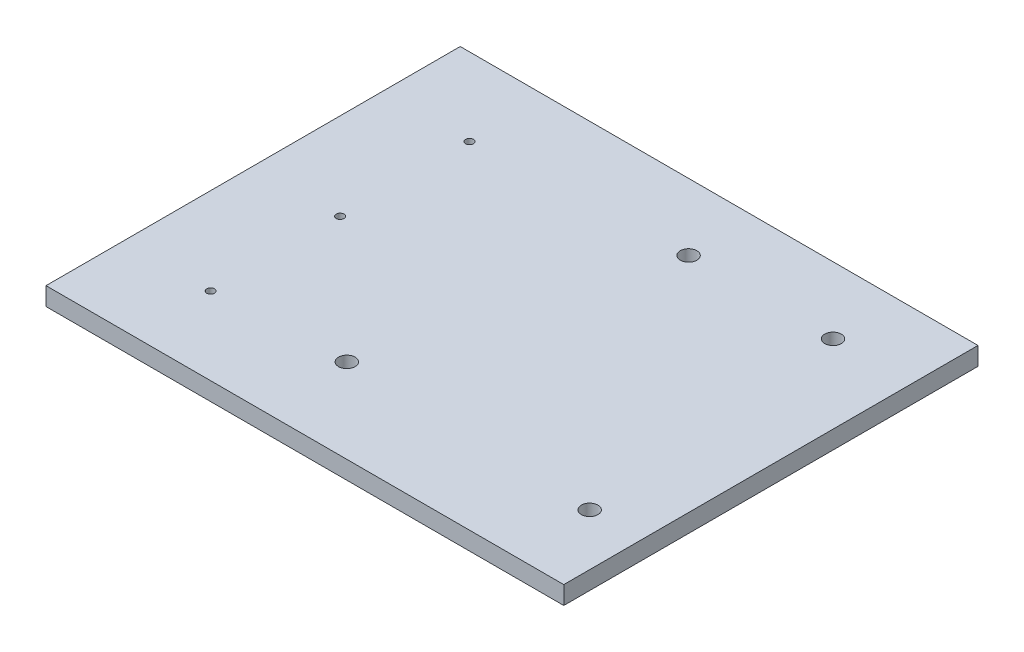
SolidWorks part; units mm, degrees
ref_plane "Front Plane" through (0, 0, 0) normal (0, 0, 1) x (1, 0, 0)
ref_plane "Top Plane" through (0, 0, 0) normal (0, 1, 0) x (1, 0, 0)
ref_plane "Right Plane" through (0, 0, 0) normal (1, 0, 0) x (0, 0, -1)
sketch "Sketch1" plane through (0, 0, 0) normal (0, 1, 0) x (1, 0, 0)
  line L1 (-50, 40) -> (50, 40)
  line L2 (-50, 40) -> (-50, -40)
  line L3 (-50, -40) -> (50, -40)
  line L4 (50, 40) -> (50, -40)
  line L5 (-50, 40) -> (50, -40) construction
  line L6 (-50, -40) -> (50, 40) construction
  point P0 (0, 0)
  dimension "D1" = 100
  dimension "D2" = 80
extrude "Boss-Extrude1" add sketch "Sketch1" along normal blind 3.5
sketch "Sketch2" plane through (0, 3.5, 0) normal (0, 1, 0) x (1, 0, 0)
  line L0 (7, 27.1) -> (34.9, 27.1) construction
  line L1 (50, -40) -> (50, 40) construction
  line L2 (-50, -40) -> (50, -40) construction
  line L3 (-13.2, -40) -> (-13.2, 40) construction
  line L4 (50, 40) -> (-50, 40) construction
  line L5 (-33.2, -40) -> (-33.2, 40) construction
  line L6 (-33.2, 0) -> (-50, 0) construction
  line L7 (-50, 40) -> (-50, -40) construction
  circle A0 centre (40, -25) radius 1.6
  circle A1 centre (-8.2, -23.7) radius 1.6
  circle A2 centre (7, 27.1) radius 1.6
  circle A3 centre (34.9, 27.1) radius 1.6
  circle A4 centre (-33.2, -25) radius 0.75
  circle A5 centre (-33.2, 25) radius 0.75
  circle A6 centre (-33.2, 0) radius 0.75
  dimension "D1" = 3.2
  dimension "D12" = 1.5
  dimension "D2" = 1.3
  dimension "D3" = 15.2
  dimension "D4" = 50.8
  dimension "D5" = 27.9
  dimension "D6" = 5.1
  dimension "D7" = 10
  dimension "D8" = 15
  dimension "D9" = 5
  dimension "D10" = 20
  dimension "D11" = 50
extrude "Cut-Extrude1" cut sketch "Sketch2" against normal through all
